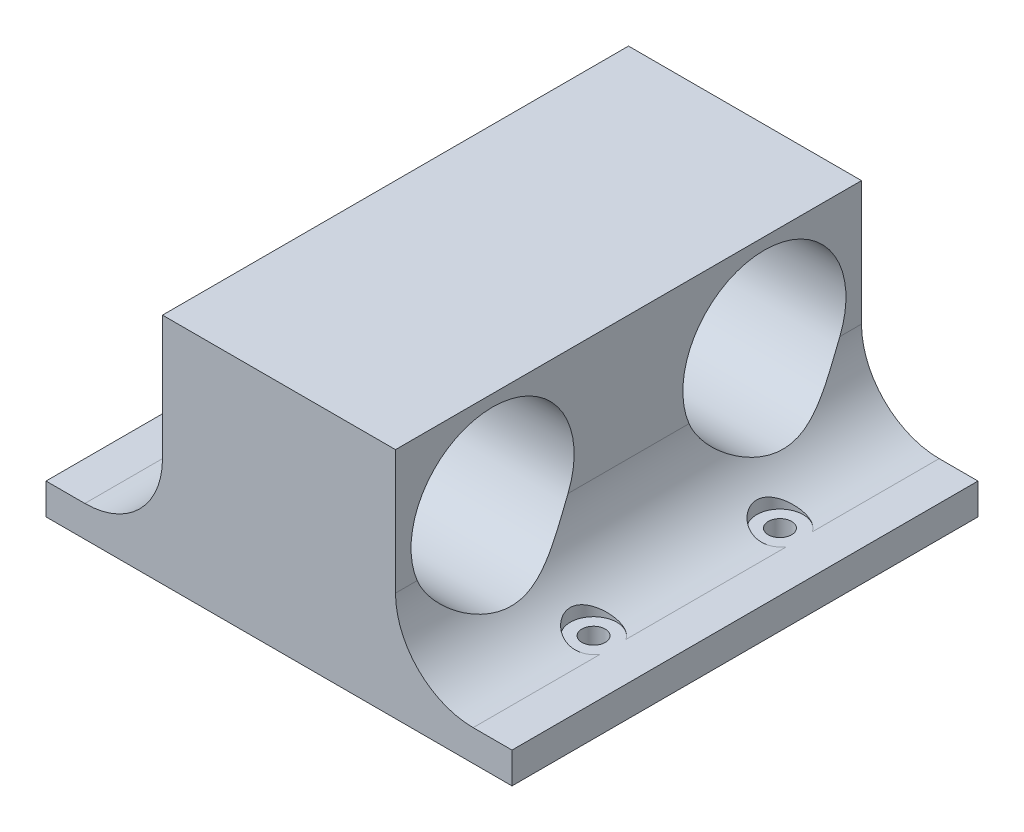
SolidWorks part; units mm, degrees
ref_plane "Front Plane" through (0, 0, 0) normal (0, 0, 1) x (1, 0, 0)
ref_plane "Top Plane" through (0, 0, 0) normal (0, 1, 0) x (1, 0, 0)
ref_plane "Right Plane" through (0, 0, 0) normal (1, 0, 0) x (0, 0, -1)
sketch "Sketch5" plane through (0, 0, 0) normal (0, 0, 1) x (1, 0, 0)
  line L0 (0, 0) -> (0, 32.9892) construction
  line L1 (15, 30) -> (-15, 30)
  line L2 (-15, 30) -> (-15, 14)
  line L3 (30, 0) -> (-30, 0)
  line L4 (-30, 0) -> (-30, 4)
  line L5 (-30, 4) -> (-25, 4)
  line L6 (30, 4) -> (25, 4)
  line L7 (30, 0) -> (30, 4)
  line L8 (15, 30) -> (15, 14)
  arc A0 (-15, 14) -> (-25, 4) centre (-25, 14) cw
  arc A1 (15, 14) -> (25, 4) centre (25, 14) ccw
  point P17 (0, 30)
  dimension "D1" = 10
  dimension "D2" = 30
  dimension "D3" = 60
  dimension "D4" = 4
  dimension "D5" = 30
extrude "Boss-Extrude1" add sketch "Sketch5" along normal mid plane 60
sketch "Sketch6" plane through (30, 0, 0) normal (1, 0, 0) x (0, 0, -1)
  line L0 (0, 0) -> (0, 30.9748) construction
  line L1 (-30, 0) -> (30, 0) construction
  circle A0 centre (-17.5, 18) radius 10.5
  circle A1 centre (17.5, 18) radius 10.5
  dimension "D1" = 18
  dimension "D2" = 35
  dimension "D3" = 21
extrude "Cut-Extrude1" cut sketch "Sketch6" against normal through all both and the other way through all
sketch "Sketch7" plane through (0, 0, 0) normal (0, -1, 0) x (1, 0, 0)
  line L0 (0, 0) -> (0, 30) construction
  line L1 (-30, 30) -> (30, 30) construction
  line L2 (0, 0) -> (20.4756, 0) construction
  circle A0 centre (-22.5, 12) radius 1.5
  circle A1 centre (22.5, 12) radius 1.5
  circle A2 centre (22.5, -12) radius 1.5
  circle A3 centre (-22.5, -12) radius 1.5
  dimension "D1" = 3
  dimension "D2" = 45
  dimension "D3" = 24
extrude "Cut-Extrude2" cut sketch "Sketch7" against normal through all both and the other way through all
sketch "Sketch8" plane through (0, 4, 0) normal (0, 1, 0) x (1, 0, 0)
  circle A0 centre (22.5, -12) radius 3
  circle A1 centre (22.5, 12) radius 3
  circle A2 centre (-22.5, 12) radius 3
  circle A3 centre (-22.5, -12) radius 3
  dimension "D1" = 6
  dimension "D2" = 6
  dimension "D3" = 6
  dimension "D4" = 6
extrude "Cut-Extrude3" cut sketch "Sketch8" along normal blind 10
